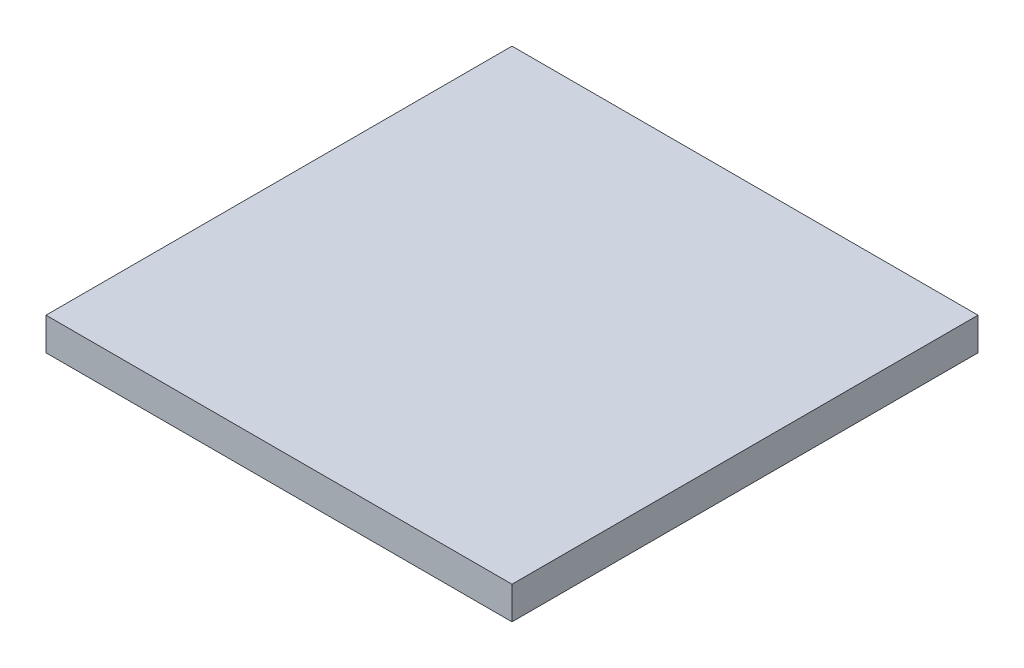
SolidWorks part; units mm, degrees
ref_plane "Front Plane" through (0, 0, 0) normal (0, 0, 1) x (1, 0, 0)
ref_plane "Top Plane" through (0, 0, 0) normal (0, 1, 0) x (1, 0, 0)
ref_plane "Right Plane" through (0, 0, 0) normal (1, 0, 0) x (0, 0, -1)
sketch "Sketch1" plane through (0, 0, 0) normal (0, 1, 0) x (1, 0, 0)
  line L1 (-63.5, -63.5) -> (63.5, -63.5)
  line L2 (-63.5, -63.5) -> (-63.5, 63.5)
  line L3 (-63.5, 63.5) -> (63.5, 63.5)
  line L4 (63.5, -63.5) -> (63.5, 63.5)
  line L5 (-63.5, -63.5) -> (63.5, 63.5) construction
  line L6 (-63.5, 63.5) -> (63.5, -63.5) construction
  point P0 (0, 0)
  dimension "D1" = 127
  dimension "D2" = 127
extrude "Boss-Extrude1" add sketch "Sketch1" along normal blind 15.24
sketch "Sketch2" plane through (0, 0, 0) normal (0, -1, 0) x (1, 0, 0)
  line L11 (-63.5, -63.5) -> (63.5, -63.5)
  line L12 (-63.5, -63.5) -> (-63.5, 63.5)
  line L13 (-63.5, 63.5) -> (63.5, 63.5)
  line L14 (50.165, -50.165) -> (50.165, 50.165)
  line L15 (-50.165, -50.165) -> (50.165, -50.165)
  line L16 (-50.165, 50.165) -> (-50.165, -50.165)
  line L17 (50.165, 50.165) -> (-50.165, 50.165)
  line L18 (50.165, -50.165) -> (50.165, 50.165)
  line L19 (-50.165, -50.165) -> (50.165, -50.165)
  line L20 (-50.165, 50.165) -> (-50.165, -50.165)
  line L21 (50.165, 50.165) -> (-50.165, 50.165)
  line L22 (63.5, -63.5) -> (63.5, 63.5)
  line L23 (-63.5, -63.5) -> (63.5, 63.5) construction
  line L24 (-63.5, 63.5) -> (63.5, -63.5) construction
  point P0 (0, 0)
  dimension "D1" = 13.335
extrude "Cut-Extrude1" cut sketch "Sketch2" against normal blind 6.35
